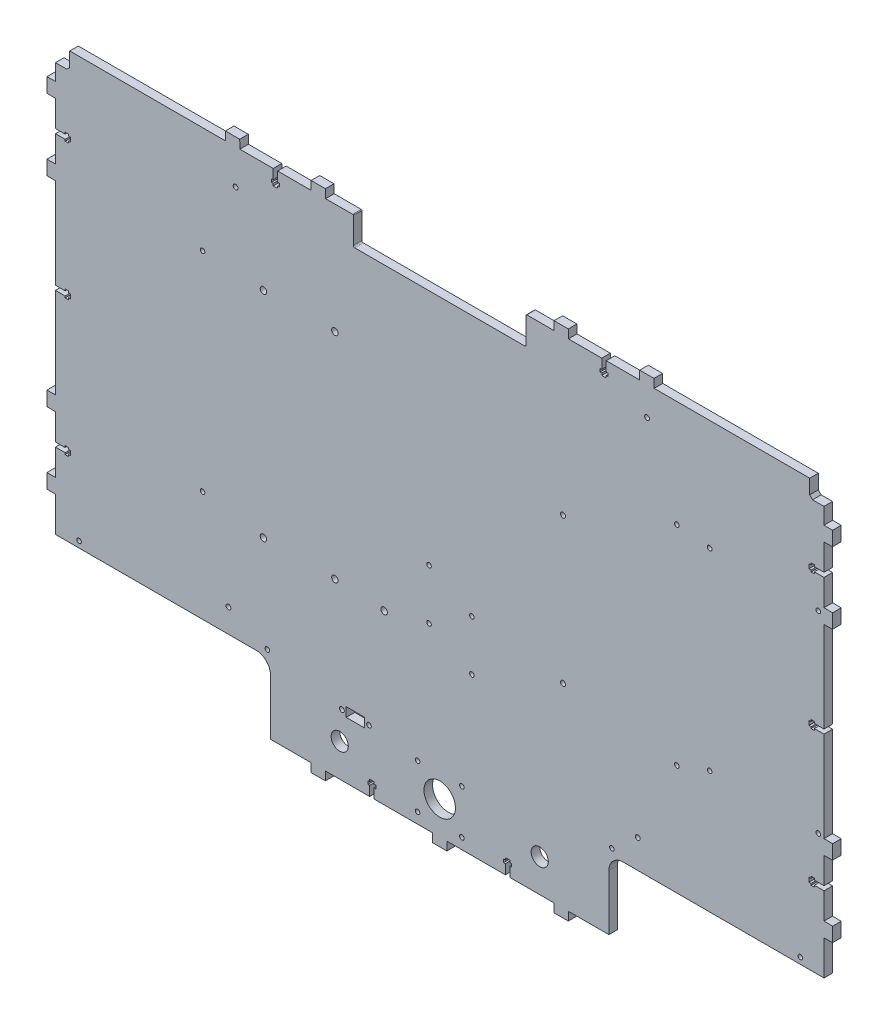
SolidWorks part; units mm, degrees
material "Клен"
ref_plane "Front" through (0, 0, 0) normal (0, 0, 1) x (1, 0, 0)
ref_plane "Top" through (0, 0, 0) normal (0, 1, 0) x (1, 0, 0)
ref_plane "Right" through (0, 0, 0) normal (1, 0, 0) x (0, 0, -1)
sketch "Эскиз1" plane through (0, 0, 0) normal (0, 0, 1) x (1, 0, 0)
  line L0 (89.7419, 500.1376) -> (118.0919, 500.1376)
  line L1 (118.0919, 500.1376) -> (118.1919, 494.1376)
  line L2 (118.1919, 494.1376) -> (128.1919, 494.1376)
  line L3 (128.1919, 494.1376) -> (128.2919, 500.1376)
  line L4 (128.2919, 500.1376) -> (159.1419, 500.1376)
  line L5 (159.1419, 500.1376) -> (159.1419, 506.9376)
  line L6 (159.1419, 506.9376) -> (157.9419, 506.9376)
  line L7 (157.9419, 506.9376) -> (157.9419, 509.1376)
  line L8 (157.9419, 509.1376) -> (159.1419, 509.1376)
  line L9 (159.1419, 509.1376) -> (159.1419, 510.6376)
  line L10 (159.1419, 510.6376) -> (162.2419, 510.6376)
  line L11 (162.2419, 510.6376) -> (162.2419, 509.1376)
  line L12 (162.2419, 509.1376) -> (163.4419, 509.1376)
  line L13 (163.4419, 509.1376) -> (163.4419, 506.9376)
  line L14 (163.4419, 506.9376) -> (162.2419, 506.9376)
  line L15 (162.2419, 506.9376) -> (162.2419, 500.1376)
  line L16 (-51.8081, 695.792) -> (-54.0081, 695.792)
  line L17 (-66.8081, 623.542) -> (-60.8081, 623.442)
  line L18 (162.2419, 500.1376) -> (203.0919, 500.1376)
  line L19 (203.0919, 500.1376) -> (203.1919, 494.1376)
  line L20 (203.1919, 494.1376) -> (213.1919, 494.1376)
  line L21 (213.1919, 494.1376) -> (213.2919, 500.1376)
  line L22 (213.2919, 500.1376) -> (254.1419, 500.1376)
  line L23 (254.1419, 500.1376) -> (254.1419, 506.9376)
  line L24 (254.1419, 506.9376) -> (252.9419, 506.9376)
  line L25 (252.9419, 506.9376) -> (252.9419, 509.1376)
  line L26 (252.9419, 509.1376) -> (254.1419, 509.1376)
  line L27 (254.1419, 509.1376) -> (254.1419, 510.6376)
  line L28 (254.1419, 510.6376) -> (257.2419, 510.6376)
  line L29 (257.2419, 510.6376) -> (257.2419, 509.1376)
  line L30 (257.2419, 509.1376) -> (258.4419, 509.1376)
  line L31 (258.4419, 509.1376) -> (258.4419, 506.9376)
  line L32 (258.4419, 506.9376) -> (257.2419, 506.9376)
  line L33 (257.2419, 506.9376) -> (257.2419, 500.1376)
  line L34 (257.2419, 500.1376) -> (288.0919, 500.1376)
  line L35 (288.0919, 500.1376) -> (288.1919, 494.1376)
  line L36 (288.1919, 494.1376) -> (298.1919, 494.1376)
  line L37 (298.1919, 494.1376) -> (298.2919, 500.1376)
  line L38 (298.2919, 500.1376) -> (326.6419, 500.1376)
  line L97 (367.1919, 847.1376) -> (358.2919, 847.1376)
  line L98 (358.2919, 847.1376) -> (358.1919, 853.1376)
  line L99 (358.1919, 853.1376) -> (348.1919, 853.1376)
  line L100 (348.1919, 853.1376) -> (348.0919, 847.1376)
  line L101 (348.0919, 847.1376) -> (324.7419, 847.1376)
  line L102 (324.7419, 847.1376) -> (324.7419, 840.3376)
  line L103 (324.7419, 840.3376) -> (325.9419, 840.3376)
  line L104 (325.9419, 840.3376) -> (325.9419, 838.1376)
  line L105 (325.9419, 838.1376) -> (324.7419, 838.1376)
  line L106 (324.7419, 838.1376) -> (324.7419, 836.6376)
  line L107 (324.7419, 836.6376) -> (321.6419, 836.6376)
  line L108 (321.6419, 836.6376) -> (321.6419, 838.1376)
  line L109 (321.6419, 838.1376) -> (320.4419, 838.1376)
  line L110 (320.4419, 838.1376) -> (320.4419, 840.3376)
  line L111 (320.4419, 840.3376) -> (321.6419, 840.3376)
  line L112 (321.6419, 840.3376) -> (321.6419, 847.1376)
  line L113 (321.6419, 847.1376) -> (298.2919, 847.1376)
  line L114 (298.2919, 847.1376) -> (298.1919, 853.1376)
  line L115 (298.1919, 853.1376) -> (288.1919, 853.1376)
  line L116 (288.1919, 853.1376) -> (288.0919, 847.1376)
  line L117 (288.0919, 847.1376) -> (269.1919, 847.1376)
  line L118 (268.6919, 846.6376) -> (268.6919, 828.542)
  line L119 (267.6919, 827.542) -> (148.6919, 827.542)
  line L120 (147.6919, 828.542) -> (147.6919, 846.542)
  line L130 (94.7419, 838.042) -> (94.7419, 836.542)
  line L131 (94.7419, 836.542) -> (91.6419, 836.542)
  line L132 (91.6419, 836.542) -> (91.6419, 838.042)
  line L199 (39.1919, 871.432) -> (39.1919, 501.6876) construction
  line L201 (142.7002, 546.3976) -> (155.7002, 546.3976)
  line L202 (155.7002, 546.3976) -> (155.7002, 539.8976)
  line L203 (155.7002, 539.8976) -> (142.7002, 539.8976)
  line L204 (142.7002, 539.8976) -> (142.7002, 546.3976)
  line L205 (-60.8081, 871.432) -> (-60.8081, 501.6876) construction
  line L206 (-50.3081, 791.992) -> (-51.8081, 791.992)
  line L207 (-60.8081, 696.992) -> (-60.8081, 633.642)
  line L208 (-60.8081, 795.092) -> (-54.0081, 795.092)
  line L209 (-51.8081, 791.992) -> (-51.8081, 790.792)
  line L210 (-54.0081, 700.092) -> (-54.0081, 701.292)
  line L211 (-51.8081, 700.092) -> (-50.3081, 700.092)
  line L212 (-60.8081, 835.042) -> (-60.8081, 823.642)
  line L213 (-51.8081, 795.092) -> (-50.3081, 795.092)
  line L214 (-54.0081, 701.292) -> (-51.8081, 701.292)
  line L215 (-50.3081, 696.992) -> (-51.8081, 696.992)
  line L216 (-54.0081, 601.992) -> (-60.8081, 601.992)
  line L217 (-60.8081, 773.642) -> (-66.8081, 773.542)
  line L218 (-50.3081, 601.992) -> (-51.8081, 601.992)
  line L219 (-60.8081, 813.442) -> (-60.8081, 795.092)
  line L220 (-54.0081, 795.092) -> (-54.0081, 796.292)
  line L221 (-54.0081, 796.292) -> (-51.8081, 796.292)
  line L222 (-51.8081, 696.992) -> (-51.8081, 695.792)
  line L223 (-54.0081, 606.292) -> (-51.8081, 606.292)
  line L224 (-60.8081, 573.442) -> (-60.8081, 549.042)
  line L225 (-52.8081, 835.042) -> (-60.8081, 835.042)
  line L226 (-54.0081, 790.792) -> (-54.0081, 791.992)
  line L227 (-51.8081, 605.092) -> (-50.3081, 605.092)
  line L228 (-66.8081, 583.542) -> (-66.8081, 573.542)
  line L229 (-51.8081, 790.792) -> (-54.0081, 790.792)
  line L230 (-54.0081, 605.092) -> (-54.0081, 606.292)
  line L231 (-51.8081, 601.992) -> (-51.8081, 600.792)
  line L232 (-66.8081, 823.542) -> (-66.8081, 813.542)
  line L233 (-50.3081, 795.092) -> (-50.3081, 791.992)
  line L234 (-60.8081, 633.642) -> (-66.8081, 633.542)
  line L235 (-60.8081, 583.642) -> (-66.8081, 583.542)
  line L236 (-66.8081, 813.542) -> (-60.8081, 813.442)
  line L237 (-66.8081, 773.542) -> (-66.8081, 763.542)
  line L238 (-51.8081, 600.792) -> (-54.0081, 600.792)
  line L239 (-66.8081, 763.542) -> (-60.8081, 763.442)
  line L240 (-50.3081, 700.092) -> (-50.3081, 696.992)
  line L241 (-60.8081, 623.442) -> (-60.8081, 605.092)
  line L243 (-54.0081, 791.992) -> (-60.8081, 791.992)
  line L244 (-54.0081, 695.792) -> (-54.0081, 696.992)
  line L245 (-60.8081, 823.642) -> (-66.8081, 823.542)
  line L246 (-51.8081, 796.292) -> (-51.8081, 795.092)
  line L247 (-51.8081, 701.292) -> (-51.8081, 700.092)
  line L248 (-60.8081, 601.992) -> (-60.8081, 583.642)
  line L249 (-54.0081, 696.992) -> (-60.8081, 696.992)
  line L250 (-66.8081, 633.542) -> (-66.8081, 623.542)
  line L251 (-60.8081, 763.442) -> (-60.8081, 700.092)
  line L252 (-54.0081, 600.792) -> (-54.0081, 601.992)
  line L254 (-50.8081, 847.042) -> (-50.8081, 837.042)
  line L255 (-50.8081, 837.042) -> (-52.8081, 835.042)
  line L256 (-60.8081, 700.092) -> (-54.0081, 700.092)
  line L257 (-60.8081, 605.092) -> (-54.0081, 605.092)
  line L258 (-50.3081, 605.092) -> (-50.3081, 601.992)
  line L259 (-60.8081, 791.992) -> (-60.8081, 773.642)
  line L260 (-51.8081, 606.292) -> (-51.8081, 605.092)
  line L261 (-66.8081, 573.542) -> (-60.8081, 573.442)
  line L264 (377.1919, 871.432) -> (377.1919, 476.2445) construction
  line L265 (477.1919, 835.042) -> (477.1919, 823.642)
  line L325 (367.1919, 847.1376) -> (467.1919, 847.1376)
  line L326 (336.6419, 549.1376) -> (377.1919, 549.1376)
  line L327 (326.6419, 500.1376) -> (326.6419, 539.1376)
  line L328 (377.1919, 549.1376) -> (477.1919, 549.1376)
  line L329 (89.7419, 539.042) -> (89.7419, 500.1376)
  line L330 (79.7419, 549.042) -> (39.1919, 549.042)
  line L331 (-60.8081, 549.042) -> (39.1919, 549.042)
  line L332 (208.1919, 486.1481) -> (208.1919, 880.8098) construction
  line L333 (107.749, 553.442) -> (-66.0548, 553.442) construction
  line L334 (315.5919, 553.5376) -> (489.3697, 553.5376) construction
  line L335 (87.5419, 557.9345) -> (87.5419, 540.5243) construction
  line L336 (328.7419, 492.2341) -> (328.7419, 562.4741) construction
  line L337 (42.1919, 871.432) -> (42.1919, 565.6434) construction
  line L338 (-84.499, 772.492) -> (54.9834, 772.492) construction
  line L339 (-84.499, 626.492) -> (54.9834, 626.492) construction
  line L340 (94.7419, 840.3376) -> (94.7419, 847.1376)
  line L341 (95.9419, 840.3376) -> (94.7419, 840.3376)
  line L342 (95.9419, 838.1376) -> (95.9419, 840.3376)
  line L343 (94.7419, 838.1376) -> (95.9419, 838.1376)
  line L344 (94.7419, 836.6376) -> (94.7419, 838.1376)
  line L345 (91.6419, 836.6376) -> (94.7419, 836.6376)
  line L346 (91.6419, 838.1376) -> (91.6419, 836.6376)
  line L347 (90.4419, 838.1376) -> (91.6419, 838.1376)
  line L348 (90.4419, 840.3376) -> (90.4419, 838.1376)
  line L349 (91.6419, 840.3376) -> (90.4419, 840.3376)
  line L350 (91.6419, 847.1376) -> (91.6419, 840.3376)
  line L351 (49.1919, 847.1376) -> (-50.8081, 847.1376)
  line L352 (128.2919, 847.1376) -> (147.1919, 847.1376)
  line L353 (128.1919, 853.1376) -> (128.2919, 847.1376)
  line L354 (118.1919, 853.1376) -> (128.1919, 853.1376)
  line L355 (118.0919, 847.1376) -> (118.1919, 853.1376)
  line L356 (94.7419, 847.1376) -> (118.0919, 847.1376)
  line L357 (68.2919, 847.1376) -> (91.6419, 847.1376)
  line L358 (68.1919, 853.1376) -> (68.2919, 847.1376)
  line L359 (58.1919, 853.1376) -> (68.1919, 853.1376)
  line L360 (58.0919, 847.1376) -> (58.1919, 853.1376)
  line L361 (49.1919, 847.1376) -> (58.0919, 847.1376)
  line L362 (147.6919, 846.6376) -> (147.6919, 846.542)
  line L363 (-50.8081, 847.1376) -> (-50.8081, 847.042)
  line L364 (467.1919, 847.1376) -> (467.1919, 847.042)
  line L365 (467.1919, 837.042) -> (469.1919, 835.042)
  line L366 (467.1919, 847.042) -> (467.1919, 837.042)
  line L367 (469.1919, 835.042) -> (477.1919, 835.042)
  line L368 (477.1919, 791.992) -> (477.1919, 773.642)
  line L369 (468.1919, 796.292) -> (468.1919, 795.092)
  line L370 (477.1919, 823.642) -> (483.1919, 823.542)
  line L371 (470.3919, 791.992) -> (477.1919, 791.992)
  line L372 (483.1919, 813.542) -> (477.1919, 813.442)
  line L373 (466.6919, 795.092) -> (466.6919, 791.992)
  line L374 (483.1919, 823.542) -> (483.1919, 813.542)
  line L375 (468.1919, 790.792) -> (470.3919, 790.792)
  line L376 (470.3919, 790.792) -> (470.3919, 791.992)
  line L377 (470.3919, 796.292) -> (468.1919, 796.292)
  line L378 (470.3919, 795.092) -> (470.3919, 796.292)
  line L379 (477.1919, 813.442) -> (477.1919, 795.092)
  line L380 (468.1919, 795.092) -> (466.6919, 795.092)
  line L381 (468.1919, 791.992) -> (468.1919, 790.792)
  line L382 (477.1919, 795.092) -> (470.3919, 795.092)
  line L383 (466.6919, 791.992) -> (468.1919, 791.992)
  line L384 (483.1919, 763.542) -> (477.1919, 763.442)
  line L385 (483.1919, 773.542) -> (483.1919, 763.542)
  line L386 (477.1919, 773.642) -> (483.1919, 773.542)
  line L387 (477.1919, 763.442) -> (477.1919, 700.092)
  line L388 (477.1919, 700.092) -> (470.3919, 700.092)
  line L389 (470.3919, 696.992) -> (477.1919, 696.992)
  line L390 (468.1919, 701.292) -> (468.1919, 700.092)
  line L391 (470.3919, 695.792) -> (470.3919, 696.992)
  line L392 (466.6919, 700.092) -> (466.6919, 696.992)
  line L393 (468.1919, 696.992) -> (468.1919, 695.792)
  line L394 (466.6919, 696.992) -> (468.1919, 696.992)
  line L395 (470.3919, 701.292) -> (468.1919, 701.292)
  line L396 (468.1919, 700.092) -> (466.6919, 700.092)
  line L397 (470.3919, 700.092) -> (470.3919, 701.292)
  line L398 (468.1919, 695.792) -> (470.3919, 695.792)
  line L399 (477.1919, 696.992) -> (477.1919, 633.642)
  line L400 (477.1919, 601.992) -> (477.1919, 583.642)
  line L401 (468.1919, 606.292) -> (468.1919, 605.092)
  line L402 (466.6919, 605.092) -> (466.6919, 601.992)
  line L403 (477.1919, 605.092) -> (470.3919, 605.092)
  line L404 (470.3919, 600.792) -> (470.3919, 601.992)
  line L405 (483.1919, 633.542) -> (483.1919, 623.542)
  line L406 (477.1919, 623.442) -> (477.1919, 605.092)
  line L407 (468.1919, 600.792) -> (470.3919, 600.792)
  line L408 (477.1919, 633.642) -> (483.1919, 633.542)
  line L409 (468.1919, 601.992) -> (468.1919, 600.792)
  line L410 (470.3919, 605.092) -> (470.3919, 606.292)
  line L411 (468.1919, 605.092) -> (466.6919, 605.092)
  line L412 (470.3919, 606.292) -> (468.1919, 606.292)
  line L413 (466.6919, 601.992) -> (468.1919, 601.992)
  line L414 (470.3919, 601.992) -> (477.1919, 601.992)
  line L415 (483.1919, 623.542) -> (477.1919, 623.442)
  line L416 (483.1919, 573.542) -> (477.1919, 573.442)
  line L417 (477.1919, 583.642) -> (483.1919, 583.542)
  line L418 (483.1919, 583.542) -> (483.1919, 573.542)
  line L419 (477.1919, 573.442) -> (477.1919, 549.042)
  circle A0 centre (138.1919, 523.1376) radius 6
  circle A1 centre (208.1919, 523.1376) radius 11
  circle A2 centre (278.1919, 523.1376) radius 6
  circle A3 centre (192.6919, 538.6376) radius 1.6
  circle A4 centre (223.6919, 538.6376) radius 1.6
  circle A5 centre (158.7002, 543.1376) radius 1.6265
  circle A6 centre (139.7002, 543.1376) radius 1.7
  circle A7 centre (192.6919, 507.6376) radius 1.6
  circle A8 centre (223.6919, 507.6376) radius 1.6
  circle A9 centre (65.2801, 822.6887) radius 1.7
  circle A10 centre (353.3431, 826.9394) radius 1.7
  circle A11 centre (84.7857, 769.7888) radius 2.25
  circle A12 centre (134.7857, 769.7888) radius 2.25
  circle A13 centre (294.4853, 738.3683) radius 1.75
  circle A15 centre (200.7177, 661.1578) radius 1.6
  circle A16 centre (230.7177, 645.1578) radius 1.6
  circle A17 centre (200.7177, 625.8978) radius 1.6
  circle A18 centre (84.7857, 619.7888) radius 2.25
  circle A19 centre (134.7857, 619.7888) radius 2.25
  circle A20 centre (169.2857, 617.7888) radius 2.25
  circle A21 centre (230.7177, 609.8978) radius 1.6
  circle A22 centre (294.4853, 636.3683) radius 1.75
  circle A24 centre (346.7847, 569.0716) radius 1.7
  circle A26 centre (60.3069, 565.6434) radius 1.7
  arc A30 (148.6919, 827.542) -> (147.6919, 828.542) centre (148.6919, 828.542) cw
  arc A31 (268.6919, 828.542) -> (267.6919, 827.542) centre (267.6919, 828.542) cw
  arc A32 (269.1919, 847.1376) -> (268.6919, 846.6376) centre (269.1919, 846.6376) ccw
  arc A38 (326.6419, 539.1376) -> (336.6419, 549.1376) centre (336.6419, 539.1376) cw
  arc A39 (89.7419, 539.042) -> (79.7419, 549.042) centre (79.7419, 539.042) ccw
  circle A40 centre (-44.2581, 553.442) radius 1.6
  circle A41 centre (460.6419, 553.5376) radius 1.6
  circle A46 centre (87.5419, 553.442) radius 1.6
  circle A47 centre (328.7419, 553.5376) radius 1.6
  circle A48 centre (42.1919, 772.492) radius 1.6
  circle A49 centre (42.1919, 626.492) radius 1.6
  circle A50 centre (374.1919, 626.492) radius 1.6
  circle A51 centre (374.1919, 772.492) radius 1.6
  circle A52 centre (397.1919, 769.7505) radius 1.6
  circle A53 centre (473.1919, 769.7505) radius 1.6
  circle A54 centre (473.1919, 634.7505) radius 1.6
  circle A55 centre (397.1919, 634.7505) radius 1.6
  arc A56 (147.1919, 847.1376) -> (147.6919, 846.6376) centre (147.1919, 846.6376) cw
  dimension "D1" = 12
  dimension "D2" = 22
  dimension "D3" = 12
  dimension "D4" = 169
  dimension "D5" = 1
  dimension "D6" = 0.5
  dimension "D10" = 3.2
  dimension "D12" = 3.2
  dimension "D13" = 4.4
  dimension "D14" = 48.35
  dimension "D15" = 3.2
  dimension "D17" = 3.2
  dimension "D21" = 3.2
  dimension "D22" = 3.2
  dimension "D24" = 23
  dimension "D26" = 31
  dimension "D27" = 31
  dimension "D28" = 31
  dimension "D30" = 23
  dimension "D32" = 43
  dimension "D33" = 43
  dimension "D34" = 3.2
  dimension "D35" = 3.2
  dimension "D37" = 3.2
  dimension "D7" = 100
  dimension "D8" = 4.4
  dimension "D9" = 169
  dimension "D11" = 16.55
  dimension "D16" = 48.45
  dimension "D18" = 3
  dimension "D20" = 146
  dimension "D23" = 23
  dimension "D25" = 7.5
  dimension "D29" = 7.5
  dimension "D31" = 39.76
extrude "Бобышка-Вытянуть1" add sketch "Эскиз1" along normal blind 6
